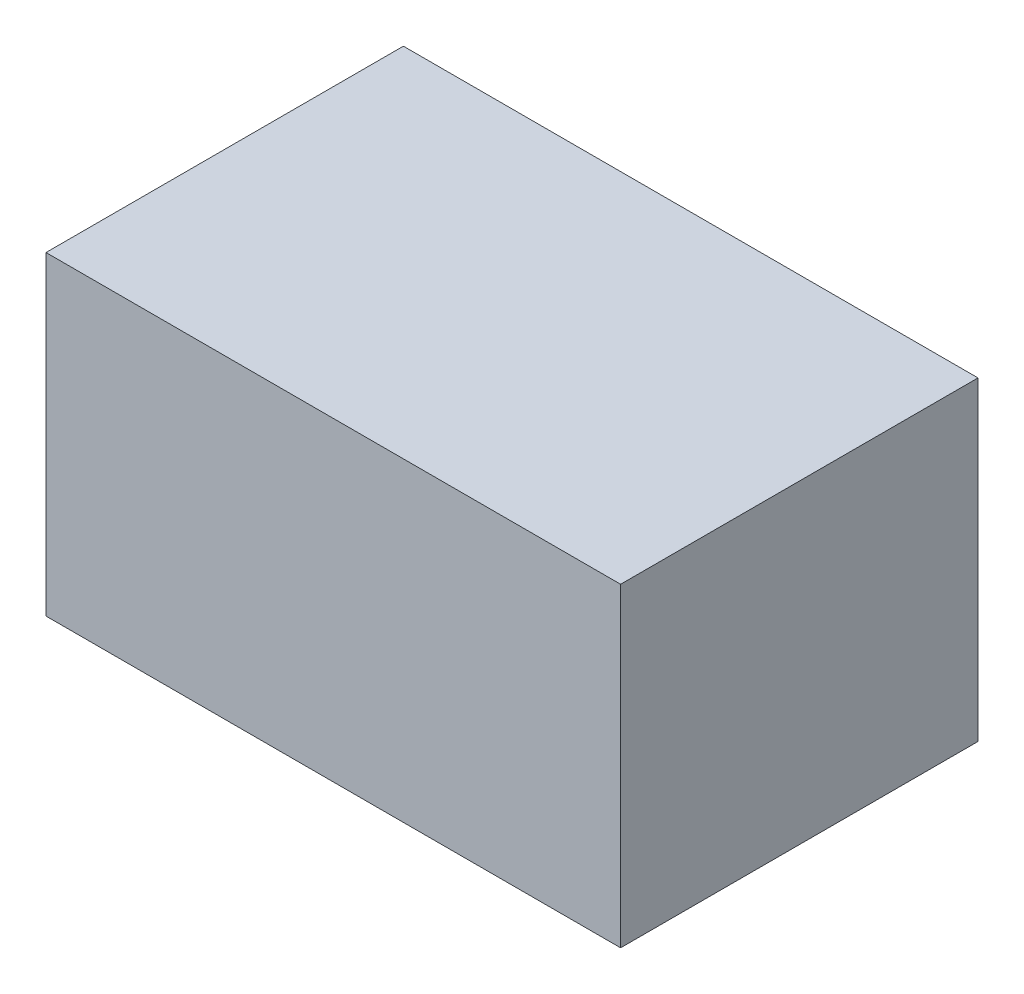
SolidWorks part; units mm, degrees
ref_plane "Front Plane" through (0, 0, 0) normal (0, 0, 1) x (1, 0, 0)
ref_plane "Top Plane" through (0, 0, 0) normal (0, 1, 0) x (1, 0, 0)
ref_plane "Right Plane" through (0, 0, 0) normal (1, 0, 0) x (0, 0, -1)
sketch "CurveSketch" plane through (0, 0, 0) normal (0, 0, 1) x (1, 0, 0)
  line L0 (-20.0525, -1.8635) -> (11.6665, -1.8635)
  line L1 (11.6665, -1.8635) -> (11.6665, 15.5175)
  line L2 (11.6665, 15.5175) -> (-20.0525, 15.5175)
  line L3 (-20.0525, 15.5175) -> (-20.0525, -1.8635)
extrude "CurveBoss" add sketch "CurveSketch" against normal blind 19.729
